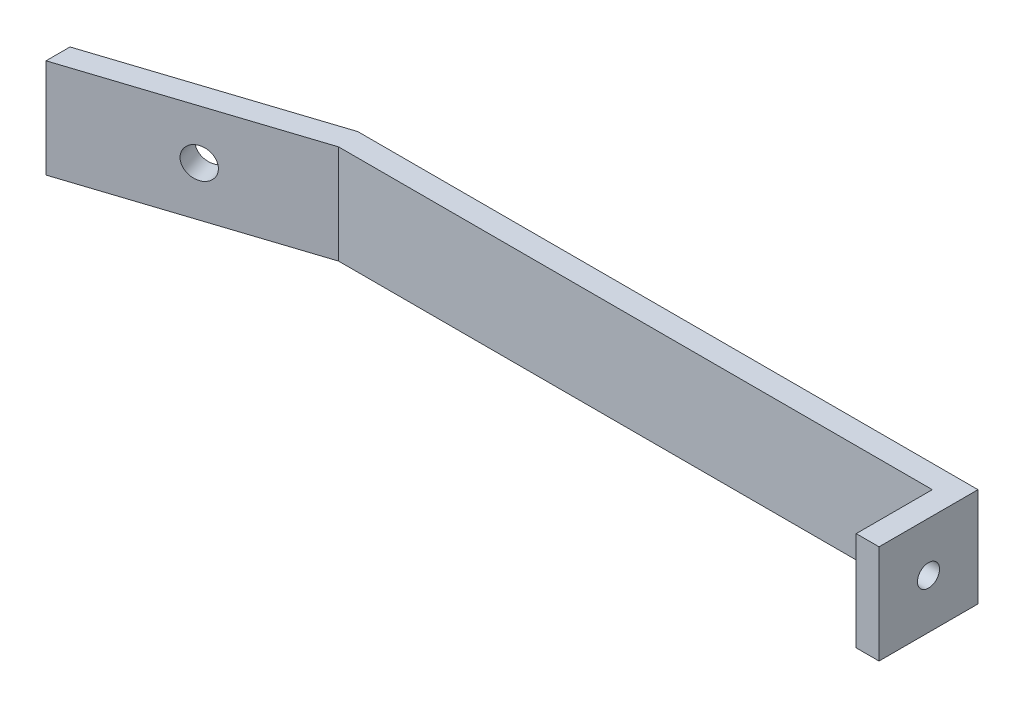
SolidWorks part; units mm, degrees
ref_plane "Front Plane" through (0, 0, 0) normal (0, 0, 1) x (1, 0, 0)
ref_plane "Top Plane" through (0, 0, 0) normal (0, 1, 0) x (1, 0, 0)
ref_plane "Right Plane" through (0, 0, 0) normal (1, 0, 0) x (0, 0, -1)
sketch "Sketch1" plane through (0, 0, 0) normal (0, 0, 1) x (1, 0, 0)
  line L1 (-55, 6.5) -> (55, 6.5)
  line L2 (-55, 6.5) -> (-55, -6.5)
  line L3 (-55, -6.5) -> (55, -6.5)
  line L4 (55, 6.5) -> (55, -6.5)
  line L5 (-55, 6.5) -> (55, -6.5) construction
  line L6 (-55, -6.5) -> (55, 6.5) construction
  point P0 (0, 0)
  dimension "D1" = 13
  dimension "D2" = 110
extrude "Boss-Extrude1" add sketch "Sketch1" along normal blind 50
sketch "Sketch2" plane through (0, -6.5, 0) normal (0, -1, 0) x (1, 0, 0)
  line L0 (-55, 9.2705) -> (-26.4683, 0)
  line L1 (-55, 50) -> (-55, 0) construction
  line L2 (-55, 0) -> (55, 0) construction
  line L3 (-55, 9.2705) -> (-55, 0)
  line L4 (-55, 0) -> (-26.4683, 0)
  dimension "D1" = 30
  dimension "D2" = 162
extrude "Cut-Extrude1" cut sketch "Sketch2" against normal through all
sketch "Sketch3" plane through (0, -6.5, 0) normal (0, -1, 0) x (1, 0, 0)
  line L0 (-55, 12.4249) -> (-25.9932, 3)
  line L1 (-55, 50) -> (-55, 9.2705) construction
  line L2 (55, 3) -> (-25.9932, 3)
  line L3 (55, 50) -> (55, 0) construction
  line L4 (-26.4683, 0) -> (-55, 9.2705) construction
  line L5 (-26.4683, 0) -> (55, 0) construction
  line L6 (55, 3) -> (55, 50)
  line L7 (55, 50) -> (-55, 50)
  line L8 (-55, 50) -> (-55, 12.4249)
  dimension "D1" = 3
  dimension "D2" = 3
extrude "Cut-Extrude2" cut sketch "Sketch3" against normal through all
sketch "Sketch4" plane through (-2.5275, 0, -7.7788) normal (-0.309, 0, -0.9511) x (-0.9511, 0, 0.309)
  line L0 (25.1729, 6.5) -> (55.1729, 6.5) construction
  line L1 (25.1729, 6.5) -> (25.1729, -6.5) construction
  circle A0 centre (40.1729, 0) radius 2
  dimension "D1" = 4
  dimension "D2" = 6.5
  dimension "D3" = 15
extrude "Cut-Extrude3" cut sketch "Sketch4" against normal through all
sketch "Sketch5" plane through (0, 0, 3) normal (0, 0, 1) x (1, 0, 0)
  line L0 (-25.9932, -6.5) -> (55, -6.5) construction
  line L1 (55, 6.5) -> (52, 6.5)
  line L2 (55, 6.5) -> (55, -6.5)
  line L3 (55, -6.5) -> (52, -6.5)
  line L4 (52, 6.5) -> (52, -6.5)
  dimension "D1" = 3
extrude "Boss-Extrude2" add sketch "Sketch5" along normal blind 10
sketch "Sketch6" plane through (55, 0, 0) normal (1, 0, 0) x (0, 0, -1)
  line L0 (0, -6.5) -> (0, 6.5) construction
  line L1 (-13, 6.5) -> (0, 6.5) construction
  circle A0 centre (-6.5, 0) radius 1.4488
  dimension "D1" = 6.5
  dimension "D2" = 6.5
extrude "Cut-Extrude5" cut sketch "Sketch6" against normal blind 12
